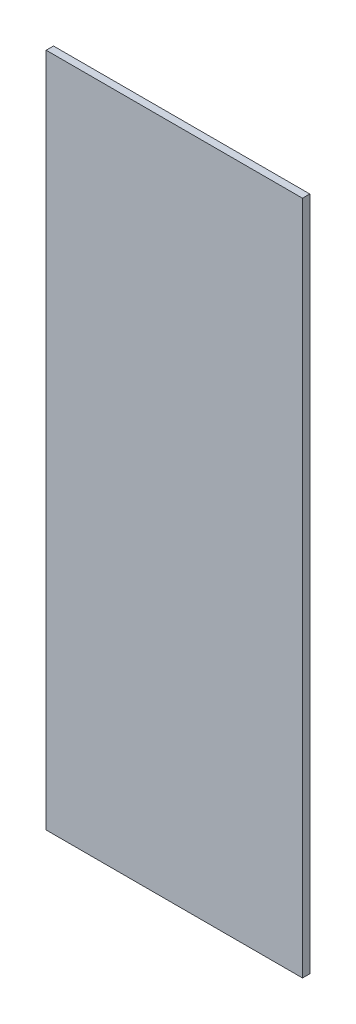
SolidWorks part; units mm, degrees
ref_plane "Front Plane" through (0, 0, 0) normal (0, 0, 1) x (1, 0, 0)
ref_plane "Top Plane" through (0, 0, 0) normal (0, 1, 0) x (1, 0, 0)
ref_plane "Right Plane" through (0, 0, 0) normal (1, 0, 0) x (0, 0, -1)
sketch "Sketch1" plane through (0, 0, 0) normal (0, 0, 1) x (1, 0, 0)
  line L1 (-120.8058, 130.559) -> (-57.8058, 130.559)
  line L2 (-120.8058, 130.559) -> (-120.8058, -35.441)
  line L3 (-120.8058, -35.441) -> (-57.8058, -35.441)
  line L4 (-57.8058, 130.559) -> (-57.8058, -35.441)
  dimension "D1" = 63
  dimension "D2" = 166
extrude "Boss-Extrude1" add sketch "Sketch1" along normal blind 1.8
